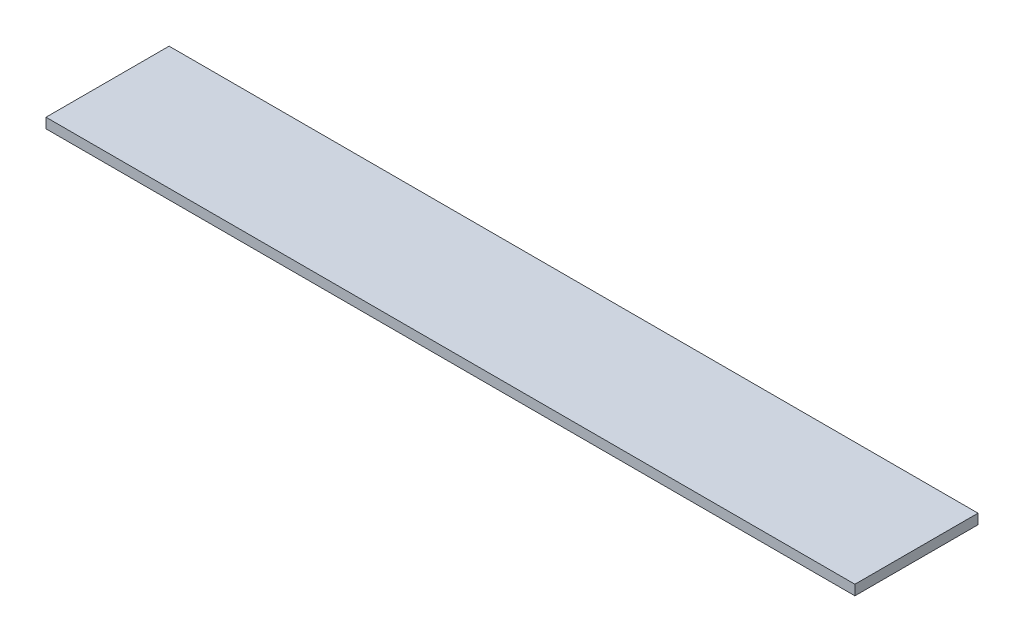
SolidWorks part; units mm, degrees
ref_plane "Front Plane" through (0, 0, 0) normal (0, 0, 1) x (1, 0, 0)
ref_plane "Top Plane" through (0, 0, 0) normal (0, 1, 0) x (1, 0, 0)
ref_plane "Right Plane" through (0, 0, 0) normal (1, 0, 0) x (0, 0, -1)
sketch "Sketch3" plane through (0, 0, 0) normal (0, 0, 1) x (1, 0, 0)
  line L1 (0, 0) -> (184, 0)
  line L2 (0, 0) -> (0, -2.2899)
  line L3 (0, -2.2899) -> (184, -2.2899)
  line L4 (184, 0) -> (184, -2.2899)
  dimension "D3" = 184
  dimension "D4" = 2.2899
extrude "Boss-Extrude1" add sketch "Sketch3" along normal blind 28
